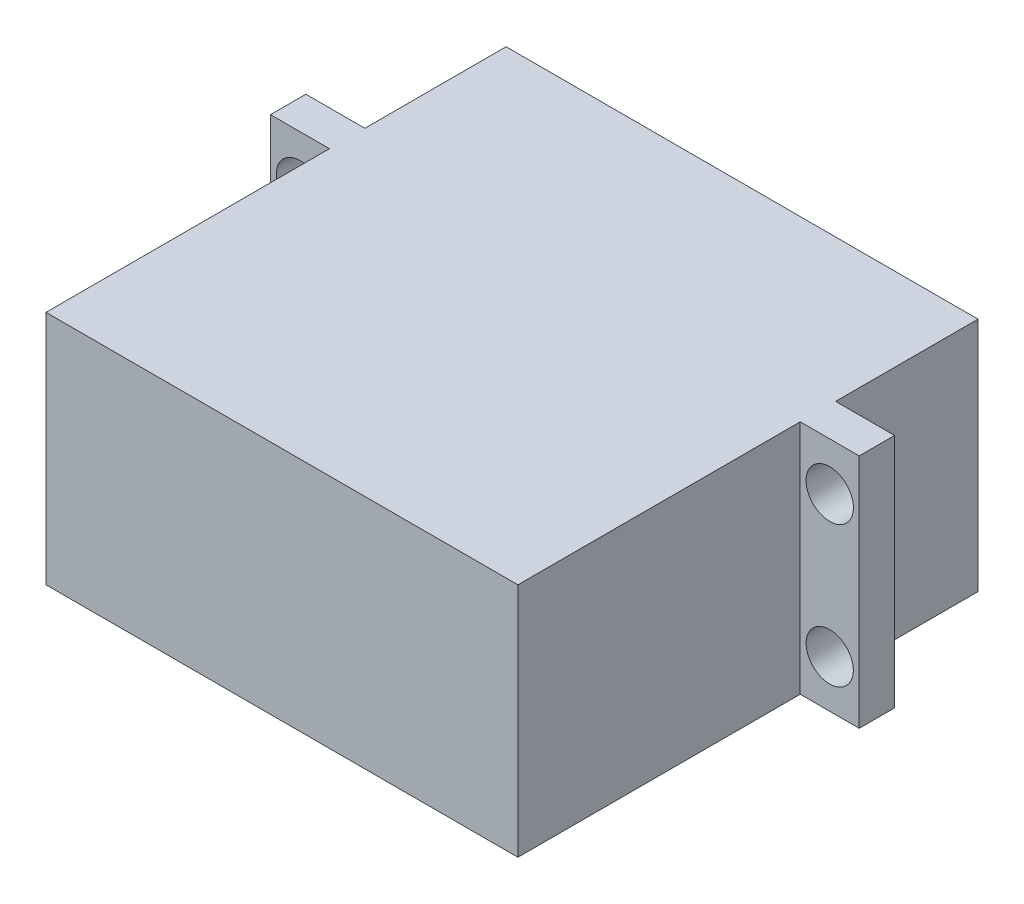
SolidWorks part; units mm, degrees
ref_plane "前视基准面" through (0, 0, 0) normal (0, 0, 1) x (1, 0, 0)
ref_plane "上视基准面" through (0, 0, 0) normal (0, 1, 0) x (1, 0, 0)
ref_plane "右视基准面" through (0, 0, 0) normal (1, 0, 0) x (0, 0, -1)
other "Configuration Table"
sketch "草图3" plane through (0, 0, 0) normal (0, 0, 1) x (1, 0, 0)
  line L1 (-73.7936, 13.2536) -> (-33.7936, 13.2536)
  line L2 (-73.7936, 13.2536) -> (-73.7936, -6.7464)
  line L3 (-73.7936, -6.7464) -> (-33.7936, -6.7464)
  line L4 (-33.7936, 13.2536) -> (-33.7936, -6.7464)
extrude "凸台-拉伸2" add sketch "草图3" along normal blind 39
sketch "草图4" plane through (-33.7936, 0, 0) normal (1, 0, 0) x (0, 0, -1)
  line L0 (-39, 13.2536) -> (0, 13.2536) construction
  line L1 (-15.0684, 13.2536) -> (-12.0684, 13.2536)
  line L2 (-15.0684, 13.2536) -> (-15.0684, -6.7464)
  line L3 (-15.0684, -6.7464) -> (-12.0684, -6.7464)
  line L4 (-12.0684, 13.2536) -> (-12.0684, -6.7464)
  line L5 (-39, -6.7464) -> (0, -6.7464) construction
  point P8 (0, 0)
  point P9 (0, 0)
  point P10 (0, 0)
  point P11 (0, 0)
  point P12 (0, 0)
extrude "凸台-拉伸3" add sketch "草图4" along normal blind 5
sketch "草图7" plane through (-73.7936, 0, 0) normal (-1, 0, 0) x (0, 0, 1)
  line L0 (39, 13.2536) -> (0, 13.2536) construction
  line L1 (11.9737, 13.2536) -> (14.9737, 13.2536)
  line L2 (11.9737, 13.2536) -> (11.9737, -6.7464)
  line L3 (11.9737, -6.7464) -> (14.9737, -6.7464)
  line L4 (14.9737, 13.2536) -> (14.9737, -6.7464)
  line L5 (39, -6.7464) -> (0, -6.7464) construction
  point P8 (15.4025, 13.2536)
  point P9 (10.4948, 13.2536)
  point P10 (14.6779, 13.2536)
  point P11 (0, 0)
  point P12 (0, 0)
sketch "草图8" plane through (-73.7936, 0, 0) normal (-1, 0, 0) x (0, 0, 1)
extrude "凸台-拉伸4" add sketch "草图7" along normal blind 5 contours L2 L1 L4 L3
sketch "草图9" plane through (0, 0, 11.9737) normal (0, 0, -1) x (-1, 0, 0)
  circle A0 centre (76.2936, 9.1421) radius 2
  circle A1 centre (76.2936, -3) radius 2
extrude "切除-拉伸1" cut sketch "草图9" against normal blind 3 contours A0 | A1
sketch "草图10" plane through (0, 0, 12.0684) normal (0, 0, -1) x (-1, 0, 0)
  circle A1 centre (31.2936, 9.199) radius 2.0091
  circle A3 centre (31.2936, -2.7464) radius 2
  point P0 (0, 0)
extrude "切除-拉伸2" cut sketch "草图10" against normal blind 3 contours A1 | A3
sketch "草图11" plane through (0, 0, 0) normal (0, 0, -1) x (-1, 0, 0)
  circle A0 centre (43.2939, 3.2536) radius 7
  circle A1 centre (43.2939, 3.2536) radius 5.6
  circle A2 centre (43.2939, 3.2536) radius 3
extrude "凸台-拉伸6" add sketch "草图11" along normal blind 6 contours A2
sketch "草图14" plane through (0, 0, 0) normal (0, 0, -1) x (-1, 0, 0)
sketch "草图15" plane through (-73.7936, 0, 0) normal (-1, 0, 0) x (0, 0, 1)
sketch "草图16" plane through (0, 0, 0) normal (0, 0, -1) x (-1, 0, 0)
  circle A0 centre (43.2939, 3.2536) radius 6
extrude "凸台-拉伸8" add sketch "草图16" along normal blind 1.5
sketch "草图17" plane through (0, 0, 0) normal (0, 0, -1) x (-1, 0, 0)
  circle A0 centre (43.2939, 3.2536) radius 7
extrude "凸台-拉伸9" add sketch "草图17" along normal blind 1 contours A0
hole_wizard "#3-48 螺纹孔的螺纹孔钻头1" positions "草图32" profile "草图33" hole size "#3-48" standard "ANSI Inch"
sketch "草图32" plane through (0, 0, -6) normal (0, 0, -1) x (-1, 0, 0)
  point P0 (43.2939, 3.2536)
sketch "草图33" plane through (-43.2939, 3.2536, -6) normal (1, 0, 0) x (0, 1, 0)
  line L0 (0, 0) -> (0, 3.599)
  line L1 (0, 3.599) -> (0.9969, 3)
  line L2 (0.9969, 3) -> (0.9969, 0)
  line L5 (0.9969, 0) -> (0, 0)
  line L10 (0, 3.599) -> (-0.997, 3) construction
  line L11 (0, -6.35) -> (0, 107.95) construction
  dimension "孔直径" = 1.9939
  dimension "孔深度" = 3
  dimension "导头角度" = 118
